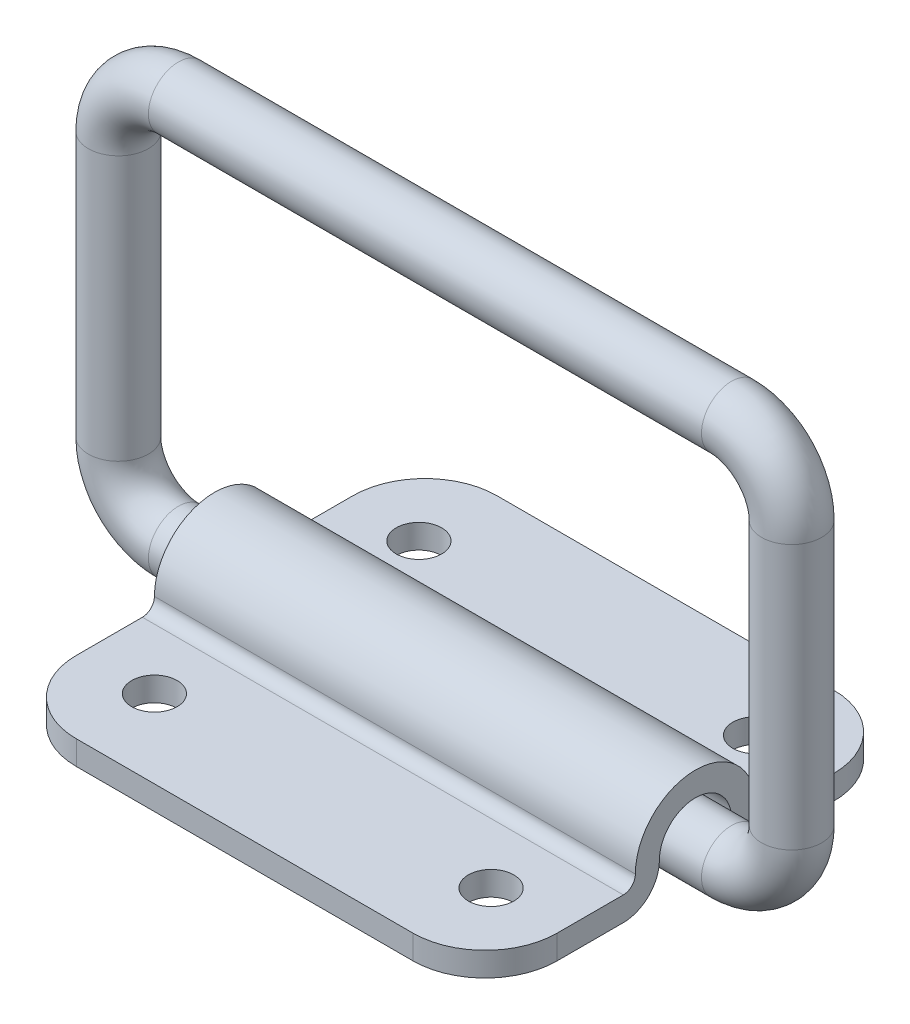
SolidWorks part; units mm, degrees
ref_plane "Front Plane" through (0, 0, 0) normal (0, 0, 1) x (1, 0, 0)
ref_plane "Top Plane" through (0, 0, 0) normal (0, 1, 0) x (1, 0, 0)
ref_plane "Right Plane" through (0, 0, 0) normal (1, 0, 0) x (0, 0, -1)
sketch "Sketch1" plane through (0, 0, 0) normal (0, 0, 1) x (1, 0, 0)
  line L0 (40.4812, 42.8625) -> (40.4813, 7.9375) construction
  line L1 (0, 0) -> (0, 91.2813) construction
  line L2 (44.45, 42.8625) -> (44.45, 7.9375)
  line L3 (-48.4187, 42.8625) -> (-48.4188, 7.9375) construction
  line L4 (-40.4812, 42.8625) -> (-40.4813, 7.9375) construction
  line L5 (48.4187, 42.8625) -> (48.4188, 7.9375) construction
  line L6 (36.5125, 3.9688) -> (-36.5125, 3.9688) construction
  line L7 (36.5125, -3.9688) -> (-36.5125, -3.9688) construction
  line L8 (0, 3.9688) -> (0, -3.9688) construction
  line L9 (-44.45, 42.8625) -> (-44.45, 7.9375)
  line L10 (44.45, 25.4) -> (-44.45, 25.4) construction
  line L11 (-36.5125, 50.8) -> (36.5125, 50.8)
  line L12 (-36.5125, 0) -> (36.5125, 0)
  arc A0 (48.4187, 42.8625) -> (-48.4187, 42.8625) centre (0, 42.8625) ccw construction
  arc A1 (40.4812, 42.8625) -> (-40.4812, 42.8625) centre (0, 42.8625) ccw construction
  circle A2 centre (0, 87.3125) radius 3.9688 construction
  circle A3 centre (0, 0) radius 3.9688 construction
  arc A5 (-36.5125, 0) -> (-44.45, 7.9375) centre (-36.5125, 7.9375) cw
  arc A6 (36.5125, -3.9688) -> (48.4188, 7.9375) centre (36.5125, 7.9375) ccw construction
  arc A7 (-36.5125, 3.9688) -> (-40.4813, 7.9375) centre (-36.5125, 7.9375) cw construction
  arc A8 (-36.5125, -3.9688) -> (-48.4188, 7.9375) centre (-36.5125, 7.9375) cw construction
  arc A9 (36.5125, 0) -> (44.45, 7.9375) centre (36.5125, 7.9375) ccw
  arc A10 (36.5125, 3.9688) -> (40.4813, 7.9375) centre (36.5125, 7.9375) ccw construction
  arc A11 (-36.5125, 50.8) -> (-44.45, 42.8625) centre (-36.5125, 42.8625) ccw
  arc A12 (36.5125, 50.8) -> (44.45, 42.8625) centre (36.5125, 42.8625) cw
  dimension "C" = 7.9375
  dimension "D1" = 7.9375
  dimension "A" = 80.9625
  dimension "B" = 95.25
sketch "Sketch2" plane through (0, 0, 0) normal (1, 0, 0) x (0, 0, -1)
  circle A0 centre (0, 0) radius 3.9688
sweep "Sweep1" add profiles "Sketch2" path "Sketch1"
sketch "Sketch3" plane through (0, 0, 0) normal (1, 0, 0) x (0, 0, -1)
  line L0 (-27.7812, -4.7625) -> (27.7812, -4.7625) construction
  line L1 (-27.7812, -4.7625) -> (-27.7812, -1.5875)
  line L2 (-27.7812, -1.5875) -> (27.7812, -1.5875) construction
  line L3 (0, 0) -> (0, -4.7625) construction
  line L4 (27.7812, -4.7625) -> (27.7812, -1.5875)
  line L5 (-27.7812, -4.7625) -> (-9.525, -4.7625)
  line L6 (-27.7812, -1.5875) -> (-9.525, -1.5875)
  line L7 (-17.4625, -4.7625) -> (-17.4625, -1.5875) construction
  line L8 (27.7812, -4.7625) -> (9.525, -4.7625)
  line L9 (27.7812, -1.5875) -> (9.525, -1.5875)
  arc A0 (-9.525, -4.7625) -> (-4.7625, 0) centre (-9.525, 0) ccw
  arc A1 (-4.7625, 0) -> (4.7625, 0) centre (0, 0) cw
  arc A2 (-9.525, -1.5875) -> (-7.9375, 0) centre (-9.525, 0) ccw
  arc A3 (-7.9375, 0) -> (7.9375, 0) centre (0, 0) cw
  arc A4 (9.525, -1.5875) -> (7.9375, 0) centre (9.525, 0) cw
  arc A5 (9.525, -4.7625) -> (4.7625, 0) centre (9.525, 0) cw
  circle A6 centre (0, 0) radius 4.7625 construction
  dimension "D1" = 34.925
  dimension "D6" = 12.7
  dimension "D4" = 9.525
  dimension "D5" = 4.7625
  dimension "D2" = 3.175
  dimension "D3" = 55.5625
extrude "Boss-Extrude1" add sketch "Sketch3" along normal mid plane 63.5 separate body
sketch "Sketch4" plane through (0, -4.7625, 0) normal (0, -1, 0) x (1, 0, 0)
  line L0 (0, 17.4625) -> (0, 0) construction
  line L1 (-31.75, 18.2563) -> (-31.75, 27.7812)
  line L2 (-31.75, 27.7812) -> (-22.225, 27.7813)
  line L3 (-22.225, 17.4625) -> (22.225, 17.4625) construction
  line L4 (31.75, 27.7813) -> (22.225, 27.7813)
  line L5 (31.75, 18.2563) -> (31.75, 27.7813)
  line L6 (31.75, -18.2562) -> (31.75, -27.7812)
  line L7 (-31.75, 0) -> (31.75, 0) construction
  line L8 (31.75, -27.7812) -> (22.225, -27.7812)
  line L9 (-31.75, -27.7812) -> (-22.225, -27.7813)
  line L10 (-31.75, -18.2563) -> (-31.75, -27.7812)
  arc A0 (-22.225, 27.7813) -> (-31.75, 18.2563) centre (-22.225, 18.2563) ccw
  circle A1 centre (-22.225, 17.4625) radius 3
  circle A2 centre (22.225, 17.4625) radius 3
  arc A3 (22.225, 27.7813) -> (31.75, 18.2563) centre (22.225, 18.2563) cw
  arc A4 (22.225, -27.7812) -> (31.75, -18.2562) centre (22.225, -18.2562) ccw
  circle A5 centre (22.225, -17.4625) radius 3
  circle A6 centre (-22.225, -17.4625) radius 3
  arc A7 (-22.225, -27.7813) -> (-31.75, -18.2563) centre (-22.225, -18.2563) cw
  dimension "D1" = 6
  dimension "D3" = 44.45
  dimension "D2" = 9.525
extrude "Cut-Extrude1" cut sketch "Sketch4" against normal through all
